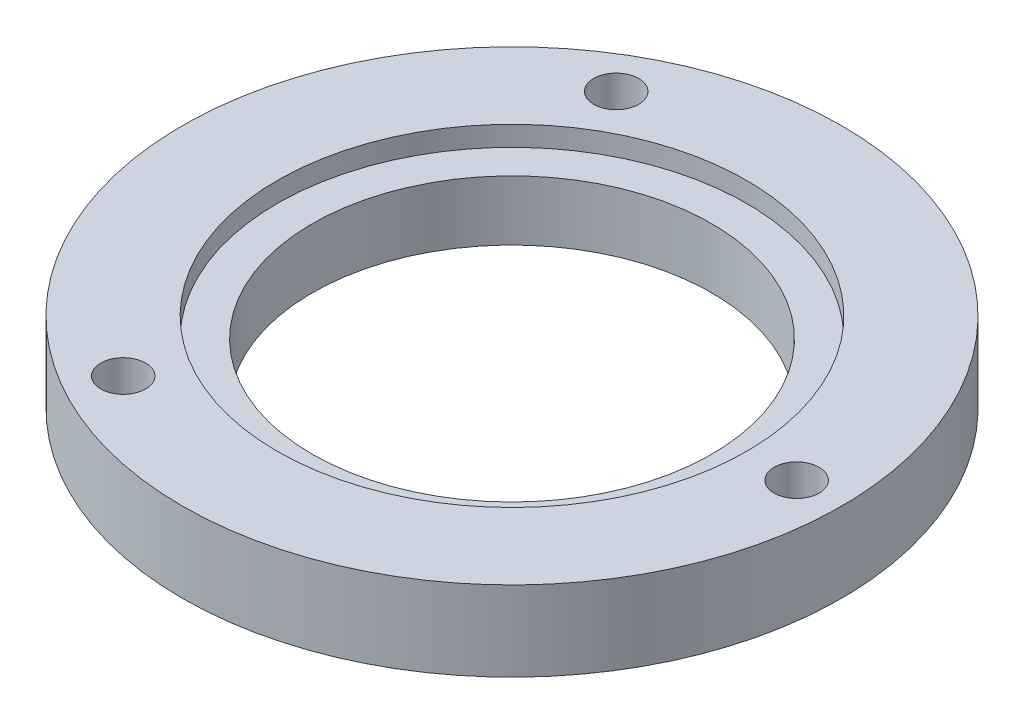
SolidWorks part; units mm, degrees
material "Alliage 1060"
ref_plane "Plan de face" through (0, 0, 0) normal (0, 0, 1) x (1, 0, 0)
ref_plane "Plan de dessus" through (0, 0, 0) normal (0, 1, 0) x (1, 0, 0)
ref_plane "Plan de droite" through (0, 0, 0) normal (1, 0, 0) x (0, 0, -1)
sketch "Esquisse1" plane through (0, 0, 0) normal (0, 0, 1) x (1, 0, 0)
  line L0 (0, 31.1775) -> (0, -18.2019) construction
  line L1 (20, 6) -> (20, 0)
  line L2 (20, 0) -> (33, 0)
  line L3 (33, 0) -> (33, 8)
  line L4 (33, 8) -> (23.5, 8)
  line L5 (23.5, 8) -> (23.5, 6)
  line L6 (23.5, 6) -> (20, 6)
  dimension "D1" = 40
  dimension "D2" = 47
  dimension "D3" = 66
  dimension "D4" = 6
  dimension "D5" = 8
revolve "Révolution1" add sketch "Esquisse1" angle 360 about L0
hole_wizard "Chambrage pour vis à tête cylindrique à 6 pans creux (ou vis CHC) M41" positions "Esquisse3" profile "Esquisse2" counterbore size "M4" standard "Ansi Métrique" end condition through all
sketch "Esquisse3" plane through (0, 0, 0) normal (0, -1, 0) x (1, 0, 0)
  point P0 (28.5, 0)
  dimension "D1" = 28.5
sketch "Esquisse2" plane through (28.5, 0, 0) normal (1, 0, 0) x (0, 0, -1)
  line L0 (0, 0) -> (0, 8)
  line L1 (0, 8) -> (2.25, 8)
  line L3 (2.25, 8) -> (2.25, 4)
  line L4 (2.25, 4) -> (4, 4)
  line L5 (4, 4) -> (4, 0)
  line L7 (4, 0) -> (0, 0)
  line L11 (0, -6.35) -> (0, 107.95) construction
  dimension "Diamètre du perçage jusqu'au prochain" = 4.5
  dimension "Profondeur du perçage jusqu'au prochain" = 8
  dimension "Diamètre du chambrage" = 8
  dimension "Profondeur du chambrage" = 4
pattern_circular "Répétition circulaire1" count 3 every 120 about axis through (0, 0, 0) along (0, 1, 0) of "Chambrage pour vis à tête cylindrique à 6 pans creux (ou vis CHC) M41"
